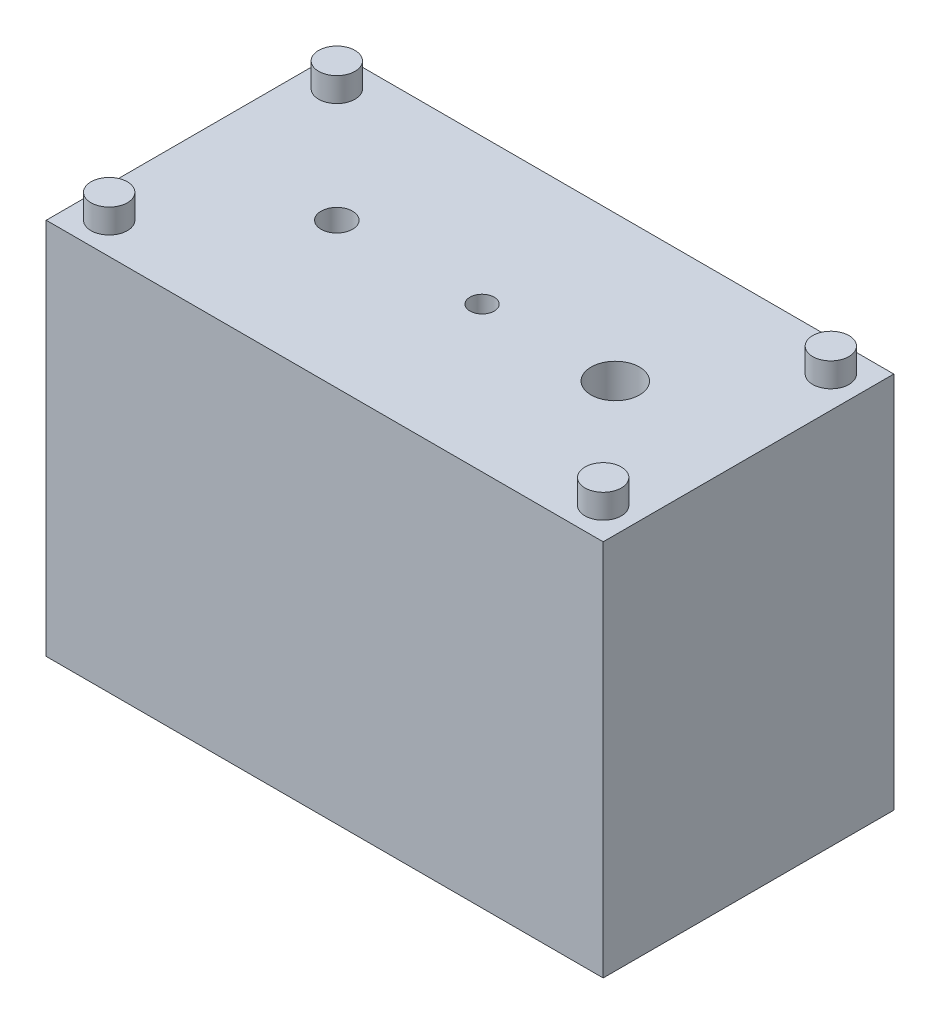
SolidWorks part; units mm, degrees
ref_plane "Front Plane" through (0, 0, 0) normal (0, 0, 1) x (1, 0, 0)
ref_plane "Top Plane" through (0, 0, 0) normal (0, 1, 0) x (1, 0, 0)
ref_plane "Right Plane" through (0, 0, 0) normal (1, 0, 0) x (0, 0, -1)
sketch "Sketch1" plane through (0, 0, 0) normal (0, 1, 0) x (1, 0, 0)
  line L1 (-11.5, 6) -> (11.5, 6)
  line L2 (-11.5, 6) -> (-11.5, -6)
  line L3 (-11.5, -6) -> (11.5, -6)
  line L4 (11.5, 6) -> (11.5, -6)
  line L5 (-11.5, 6) -> (11.5, -6) construction
  line L6 (-11.5, -6) -> (11.5, 6) construction
  point P0 (0, 0)
  dimension "D1" = 12
  dimension "D2" = 23
extrude "Boss-Extrude1" add sketch "Sketch1" along normal blind 15.6
sketch "Sketch2" plane through (0, 15.6, 0) normal (0, 1, 0) x (1, 0, 0)
  line L0 (-11.5, 0) -> (11.5, 0) construction
  line L1 (-11.5, 6) -> (-11.5, -6) construction
  line L2 (11.5, -6) -> (11.5, 6) construction
  line L3 (0, -6) -> (0, 6) construction
  line L8 (-11.5, -6) -> (11.5, -6) construction
  line L9 (11.5, 6) -> (-11.5, 6) construction
  circle A0 centre (-10.2, 4.7) radius 0.75
  circle A1 centre (10.2, 4.7) radius 0.75
  circle A2 centre (10.2, -4.7) radius 0.75
  circle A3 centre (-10.2, -4.7) radius 0.75
extrude "Boss-Extrude2" add sketch "Sketch2" along normal blind 1
sketch "Sketch3" plane through (0, 15.6, 0) normal (0, 1, 0) x (1, 0, 0)
  line L0 (11.5, 0) -> (6, 0)
  line L1 (11.5, -6) -> (11.5, 6) construction
  line L2 (6, 0) -> (0.5, 0)
  line L3 (0.5, 0) -> (-5.5, 0)
  line L4 (-11.5, 6) -> (-11.5, -6) construction
  circle A0 centre (6, 0) radius 1
  circle A1 centre (0.5, 0) radius 0.5
  circle A2 centre (-5.5, 0) radius 0.65
  dimension "D4" = 6
  dimension "D1" = 5.5
  dimension "D3" = 6
extrude "Cut-Extrude1" cut sketch "Sketch3" against normal blind 4 contours A0 | A1 | A2
